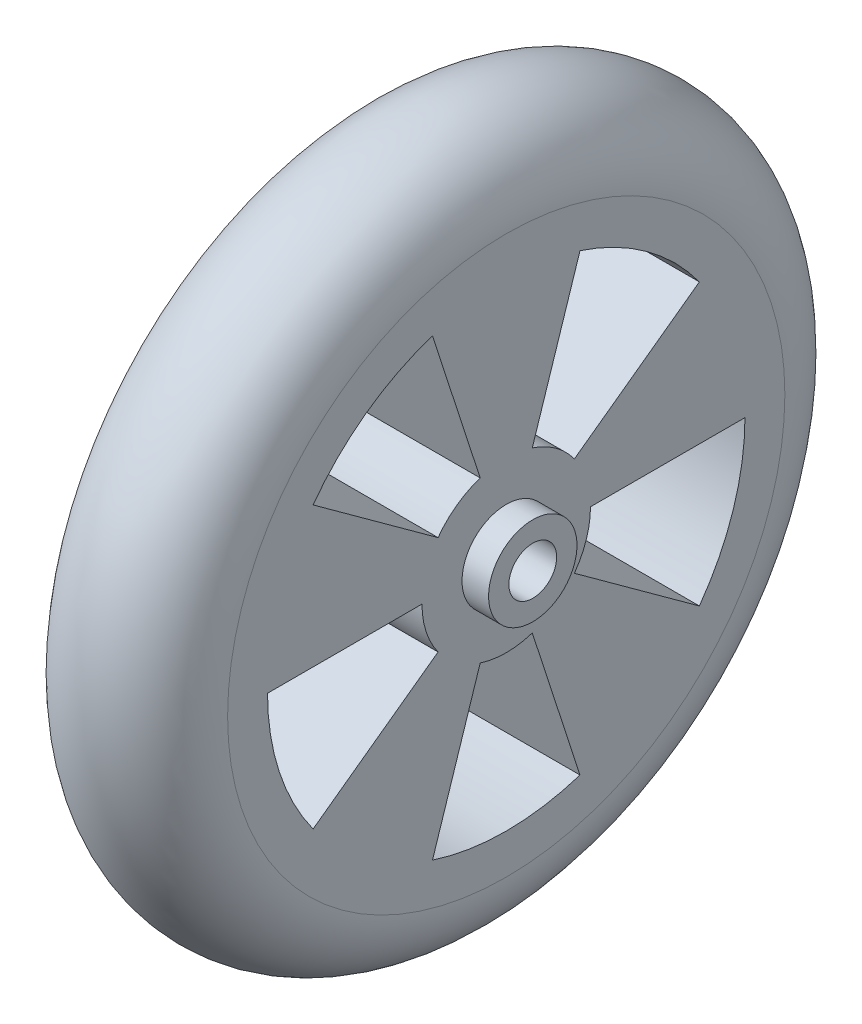
SolidWorks part; units mm, degrees
material "Rubber"
ref_plane "Front Plane" through (0, 0, 0) normal (0, 0, 1) x (1, 0, 0)
ref_plane "Top Plane" through (0, 0, 0) normal (0, 1, 0) x (1, 0, 0)
ref_plane "Right Plane" through (0, 0, 0) normal (1, 0, 0) x (0, 0, -1)
sketch "Sketch1" plane through (0, 0, 0) normal (0, 0, 1) x (1, 0, 0)
  line L0 (0, 31.5) -> (0, 0)
  line L1 (0, 0) -> (20, 0)
  line L2 (20, 0) -> (20, 5)
  line L3 (20, 5) -> (17, 5)
  line L4 (17, 5) -> (17, 31.5)
  line L5 (0, 31.5) -> (17, 31.5) construction
  arc A0 (0, 31.5) -> (17, 31.5) centre (8.5, 31.5) cw
  point P9 (8.5, 40)
  dimension "D1" = 40
  dimension "D2" = 17
  dimension "D3" = 3
  dimension "D4" = 5
revolve "Revolve1" add sketch "Sketch1" angle 360 about L1
sketch "Sketch2" plane through (0, 0, 0) normal (1, 0, 0) x (0, 0, -1)
  circle A0 centre (0, 0) radius 2.7
  dimension "D1" = 5.4
extrude "Cut-Extrude1" cut sketch "Sketch2" along normal through all
sketch "Sketch3" plane through (0, 0, 0) normal (1, 0, 0) x (0, 0, -1)
  line L0 (0, 0) -> (8.3396, 25.6666)
  line L1 (0, 0) -> (21.8333, 15.8629)
  line L2 (0, 0) -> (0, 40) construction
  line L3 (0, 0) -> (26.9875, 0)
  line L4 (0, 0) -> (21.8333, -15.8629)
  line L5 (0, 0) -> (8.3396, -25.6666)
  line L6 (0, 0) -> (-8.3396, -25.6666)
  line L7 (0, 0) -> (-21.8333, -15.8629)
  line L8 (0, 0) -> (-26.9875, 0)
  line L9 (0, 0) -> (-21.8333, 15.8629)
  line L10 (0, 0) -> (-8.3396, 25.6666)
  circle A0 centre (0, 0) radius 9.525 construction
  circle A1 centre (0, 0) radius 26.9875 construction
  arc A2 (2.9434, 9.0588) -> (7.7059, 5.5987) centre (0, 0) cw
  arc A3 (8.3396, 25.6666) -> (21.8333, 15.8629) centre (0, 0) cw
  circle A4 centre (0, 0) radius 40 construction
  arc A5 (26.9875, 0) -> (21.8333, -15.8629) centre (0, 0) cw
  arc A6 (9.525, 0) -> (7.7059, -5.5987) centre (0, 0) cw
  arc A7 (8.3396, -25.6666) -> (-8.3396, -25.6666) centre (0, 0) cw
  arc A8 (2.9434, -9.0588) -> (-2.9434, -9.0588) centre (0, 0) cw
  arc A9 (-21.8333, -15.8629) -> (-26.9875, 0) centre (0, 0) cw
  arc A10 (-7.7059, -5.5987) -> (-9.525, 0) centre (0, 0) cw
  arc A11 (-21.8333, 15.8629) -> (-8.3396, 25.6666) centre (0, 0) cw
  arc A12 (-7.7059, 5.5987) -> (-2.9434, 9.0588) centre (0, 0) cw
  point P30 (0, 0)
  dimension "D1" = 19.05
  dimension "D2" = 53.975
  dimension "D3" = 18
  dimension "D4" = 36
  dimension "D5" = 5
extrude "Cut-Extrude2" cut sketch "Sketch3" along normal through all contours L9 A12 L10 A11 | A3 L0 A2 L1 | L3 A6 L4 A5 | L5 A8 L6 A7 | L7 A10 L8 A9
